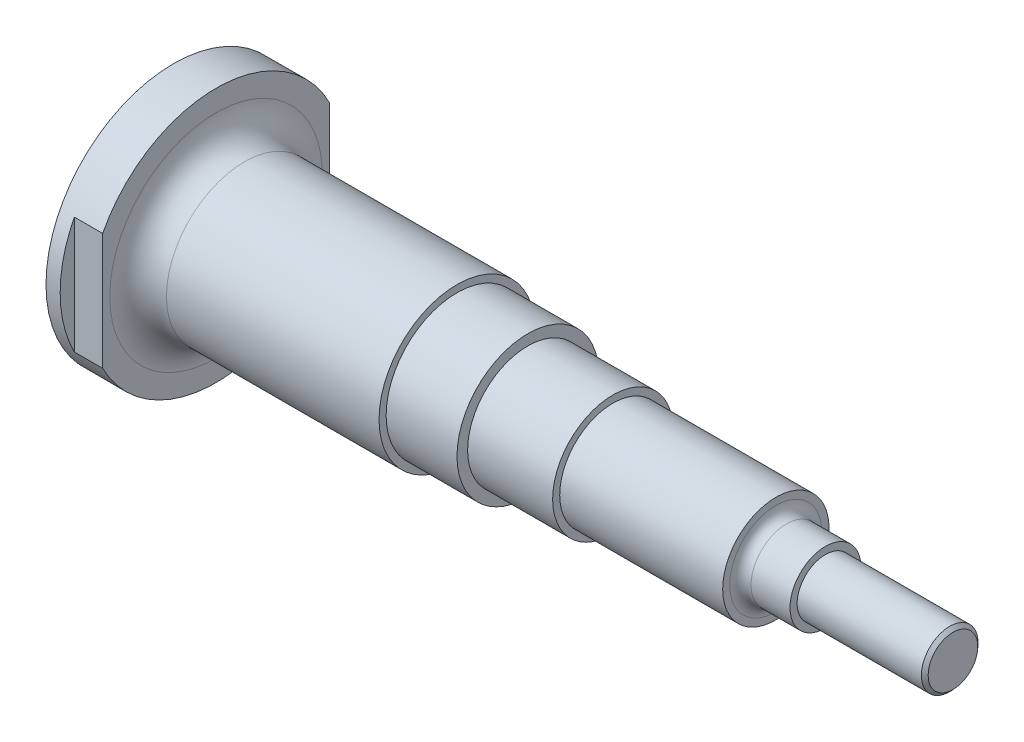
SolidWorks part; units mm, degrees
ref_plane "Face" through (0, 0, 0) normal (0, 0, 1) x (1, 0, 0)
ref_plane "Dessus" through (0, 0, 0) normal (0, 1, 0) x (1, 0, 0)
ref_plane "Droite" through (0, 0, 0) normal (1, 0, 0) x (0, 0, -1)
sketch "Esquisse1" plane through (0, 0, 0) normal (0, 0, 1) x (1, 0, 0)
  line L0 (-137, 0) -> (-113, 0) construction
  line L1 (-35, 0) -> (0, 0) construction
  line L2 (-130, 7) -> (-130, 18)
  line L3 (-124, 18) -> (-130, 18)
  line L4 (-124, 18) -> (-124, 15)
  line L5 (-120, 11) -> (-90, 11)
  line L6 (-130, 7) -> (-129.0032, 7)
  line L7 (-20, 3.5) -> (-20.4613, 4)
  line L8 (-90, 10) -> (-90, 11)
  line L9 (-90, 10) -> (-80, 10)
  line L10 (-125, 0) -> (-17.5, 0) construction
  line L11 (-92.0032, 0) -> (-20, 0)
  line L12 (-80, 8.5) -> (-80, 10)
  line L13 (-80, 8.5) -> (-68, 8.5)
  line L14 (-120.5914, 0) -> (-83.5914, 0) construction
  line L16 (-68, 7.5) -> (-68, 8.5)
  line L17 (-68, 7.5) -> (-45, 7.5)
  line L18 (-129.0032, 7) -> (-129.0032, 6)
  line L19 (-129.0032, 6) -> (-101.0032, 6)
  line L20 (-45, 6.5) -> (-45, 7.5)
  line L21 (-43.5, 5) -> (-38, 5)
  line L22 (-101.0032, 6) -> (-101.0032, 5)
  line L23 (-101.0032, 5) -> (-95.0032, 5)
  line L24 (-38, 4) -> (-38, 5)
  line L25 (-38, 4) -> (-20.4613, 4)
  line L26 (-95.0032, 5) -> (-92.0032, 0)
  line L28 (-20, 0) -> (-20, 3.5)
  arc A0 (-120, 11) -> (-124, 15) centre (-120, 15) cw
  arc A1 (-43.5, 5) -> (-45, 6.5) centre (-43.5, 6.5) cw
  dimension "D14" = 4
  dimension "D15" = 1.5
  dimension "D1" = 6
  dimension "D2" = 40
  dimension "D3" = 50
  dimension "D4" = 62
  dimension "D5" = 85
  dimension "D6" = 4
  dimension "D7" = 110
  dimension "D8" = 5
  dimension "D9" = 7.5
  dimension "D10" = 8.5
  dimension "D11" = 10
  dimension "D12" = 11
  dimension "D13" = 18
  dimension "D16" = 92
revolve "Base-Révolution" add sketch "Esquisse1" angle 360 about L10
sketch "Esquisse3" plane through (-124, 0, 0) normal (1, 0, 0) x (0, 0, -1)
  line L0 (-20, -10) -> (-16, -10)
  line L1 (-20, -10) -> (-20, 10)
  line L2 (-16, 10) -> (-20, 10)
  line L3 (-16, 10) -> (-16, -10)
  line L4 (16, 10) -> (20, 10)
  line L5 (16, 10) -> (16, -10)
  line L6 (20, -10) -> (16, -10)
  line L7 (20, -10) -> (20, 10)
  dimension "D1" = 16
  dimension "D2" = 16
extrude "Enlèv. mat.-Extru.1" cut sketch "Esquisse3" against normal blind 4
